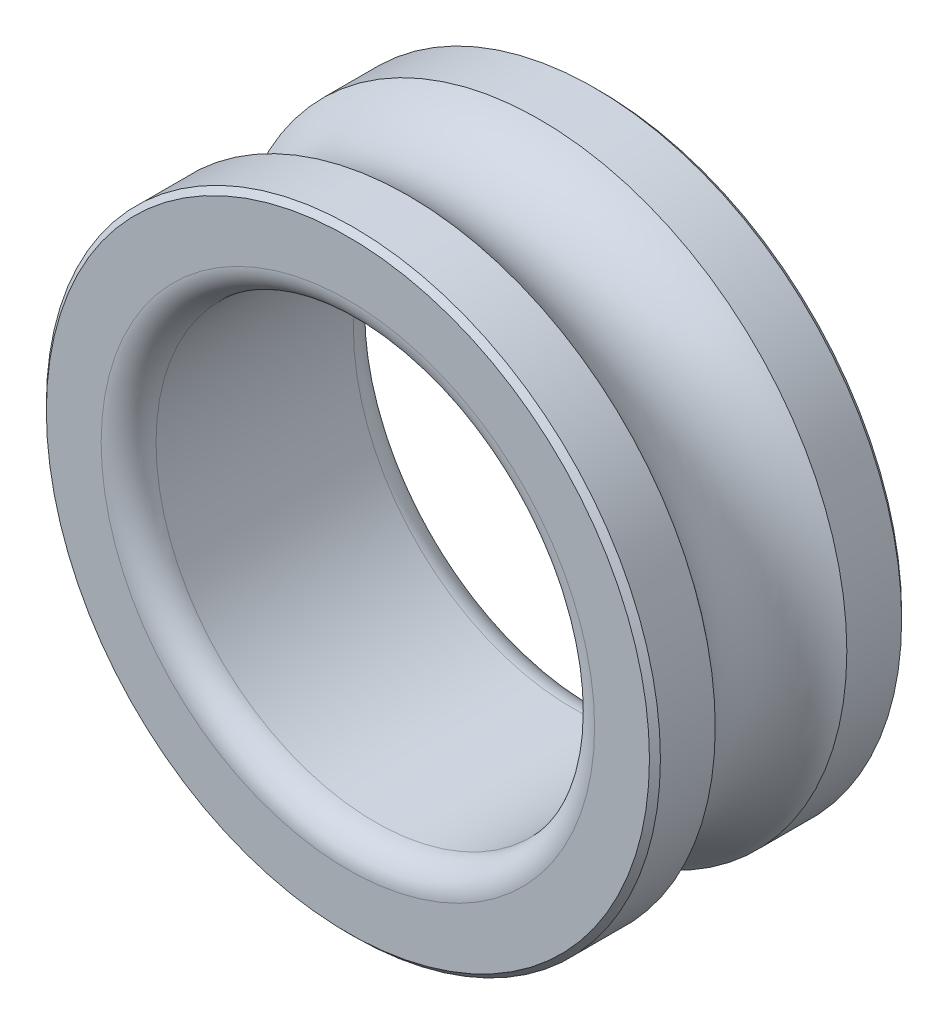
SolidWorks part; units mm, degrees
ref_plane "Front Plane" through (0, 0, 0) normal (0, 0, 1) x (1, 0, 0)
ref_plane "Top Plane" through (0, 0, 0) normal (0, 1, 0) x (1, 0, 0)
ref_plane "Right Plane" through (0, 0, 0) normal (1, 0, 0) x (0, 0, -1)
sketch "Sketch1" plane through (0, 0, 0) normal (0, 0, 1) x (1, 0, 0)
  circle A0 centre (0, 0) radius 20
  circle A1 centre (0, 0) radius 28
  dimension "D1" = 40
  dimension "D2" = 56
extrude "Boss-Extrude1" add sketch "Sketch1" along normal mid plane 23
sketch "Sketch2" plane through (0, 0, 0) normal (0, 0, 1) x (1, 0, 0)
  circle A0 centre (0, 0) radius 32.5 construction
  circle A1 centre (32.5, 0) radius 7.5
  dimension "D1" = 65
  dimension "D2" = 15
sketch "Sketch3" plane through (0, 0, 0) normal (0, 1, 0) x (1, 0, 0)
  line L0 (25, 0) -> (40, 0) construction
  line L1 (0, 0) -> (0, 20.275) construction
  line L2 (-32.5, 0) -> (32.5, 0) construction
  circle A0 centre (32.5, 0) radius 7.5
  dimension "D1" = 15
revolve "Cut-Revolve1" cut sketch "Sketch3" angle 360 about L1
chamfer "Chamfer1" distance 0.5 angle 45 2 edges at (28, 0, -11.5) (28, 0, 11.5)
fillet "Fillet1" radius 2.5 2 edges at (20, 0, -11.5) (20, 0, 11.5)
